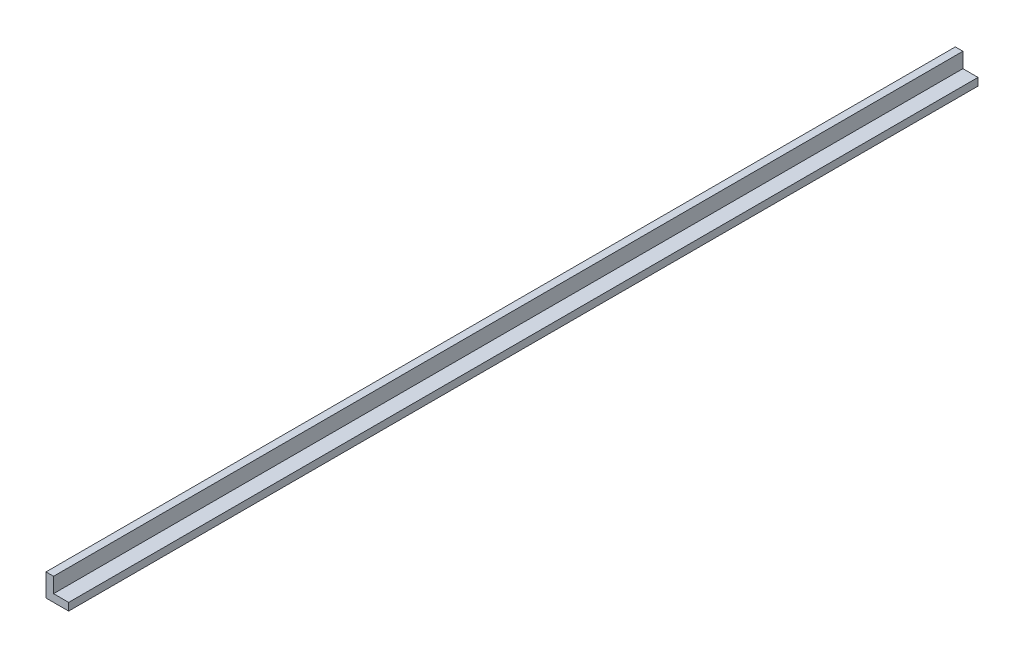
SolidWorks part; units mm, degrees
material "ASTM A36 Acero"
ref_plane "Alzado" through (0, 0, 0) normal (0, 0, 1) x (1, 0, 0)
ref_plane "Planta" through (0, 0, 0) normal (0, 1, 0) x (1, 0, 0)
ref_plane "Vista lateral" through (0, 0, 0) normal (1, 0, 0) x (0, 0, -1)
sketch "Croquis1" plane through (0, 0, 0) normal (0, 0, 1) x (1, 0, 0)
  line L0 (0, 152) -> (0, 0)
  line L1 (0, 0) -> (152, 0)
  line L2 (152, 0) -> (152, 50.8)
  line L3 (152, 50.8) -> (50.8, 50.8)
  line L4 (50.8, 50.8) -> (50.8, 152)
  line L5 (50.8, 152) -> (0, 152)
  dimension "D1" = 50.8
  dimension "D2" = 152
extrude "Saliente-Extruir1" add sketch "Croquis1" against normal blind 6100
